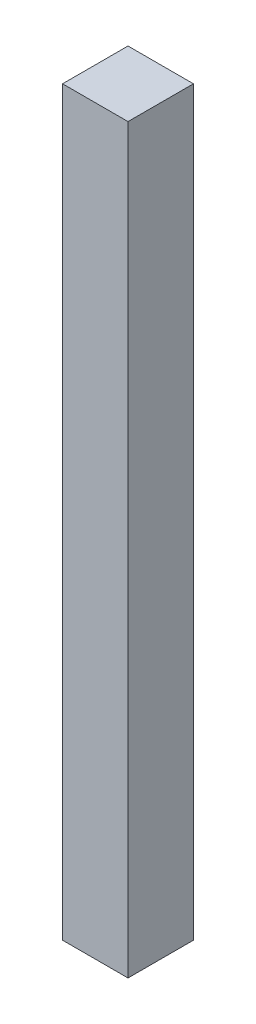
SolidWorks part; units mm, degrees
ref_plane "前视基准面" through (0, 0, 0) normal (0, 0, 1) x (1, 0, 0)
ref_plane "上视基准面" through (0, 0, 0) normal (0, 1, 0) x (1, 0, 0)
ref_plane "右视基准面" through (0, 0, 0) normal (1, 0, 0) x (0, 0, -1)
sketch "草图1" plane through (0, 0, 0) normal (0, 1, 0) x (1, 0, 0)
  line L1 (-15, -15) -> (15, -15)
  line L2 (-15, -15) -> (-15, 15)
  line L3 (-15, 15) -> (15, 15)
  line L4 (15, -15) -> (15, 15)
  line L5 (0, 15) -> (0, -15) construction
  line L6 (-15, 0) -> (15, 0) construction
  point P0 (0, 0)
  dimension "D1" = 30
  dimension "D2" = 30
extrude "凸台-拉伸1" add sketch "草图1" along normal blind 340
